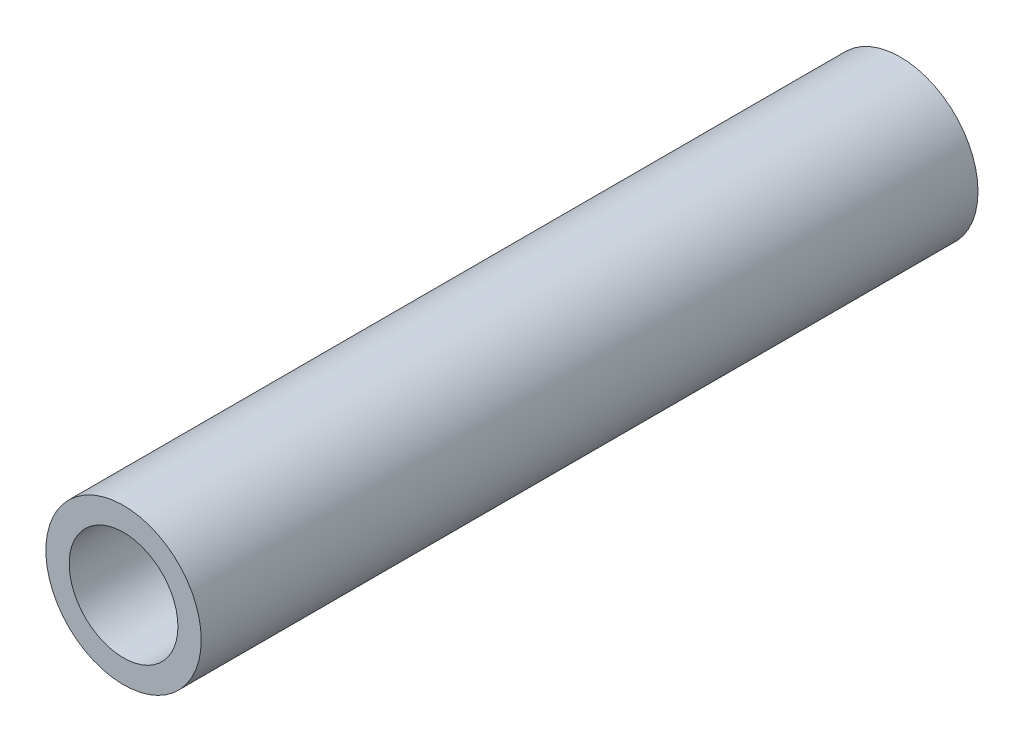
SolidWorks part; units mm, degrees
ref_plane "Front Plane" through (0, 0, 0) normal (0, 0, 1) x (1, 0, 0)
ref_plane "Top Plane" through (0, 0, 0) normal (0, 1, 0) x (1, 0, 0)
ref_plane "Right Plane" through (0, 0, 0) normal (1, 0, 0) x (0, 0, -1)
sketch "Sketch1" plane through (0, 0, 0) normal (0, 0, 1) x (1, 0, 0)
  circle A0 centre (0, 0) radius 2.1
  circle A1 centre (0, 0) radius 3
  dimension "D1" = 4.2
  dimension "D2" = 6
extrude "Boss-Extrude1" add sketch "Sketch1" along normal blind 30
equation "\"iw\"= 4.2mm'o"
equation "\"ow\"= 6mm"
equation "\"h\"= 30mm"
equation "\"D1@Sketch1\"=\"iw\""
equation "\"D2@Sketch1\"=\"ow\""
equation "\"D1@Boss-Extrude1\"=\"h\""
